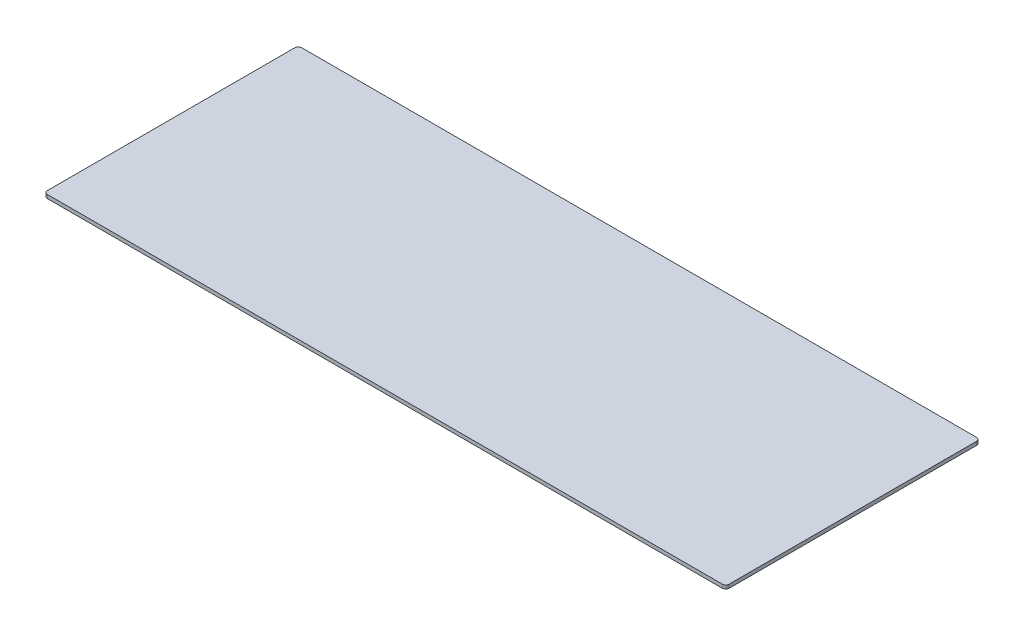
SolidWorks part; units mm, degrees
ref_plane "前视基准面" through (0, 0, 0) normal (0, 0, 1) x (1, 0, 0)
ref_plane "上视基准面" through (0, 0, 0) normal (0, 1, 0) x (1, 0, 0)
ref_plane "右视基准面" through (0, 0, 0) normal (1, 0, 0) x (0, 0, -1)
other "Configuration Table"
sketch "草图1" plane through (0, 0, 0) normal (0, 1, 0) x (1, 0, 0)
  line L0 (25.2806, 0) -> (328.2806, 0)
  line L1 (328.2806, 0) -> (328.2806, -113)
  line L2 (328.2806, -113) -> (25.2806, -113)
  line L3 (25.2806, -113) -> (25.2806, 0)
extrude "凸台-拉伸1" add sketch "草图1" along normal blind 1.6
fillet "圆角1" radius 1.5 4 edges at (328.2806, 0.8, 0) (328.2806, 0.8, 113) (25.2806, 0.8, 0) (25.2806, 0.8, 113)
